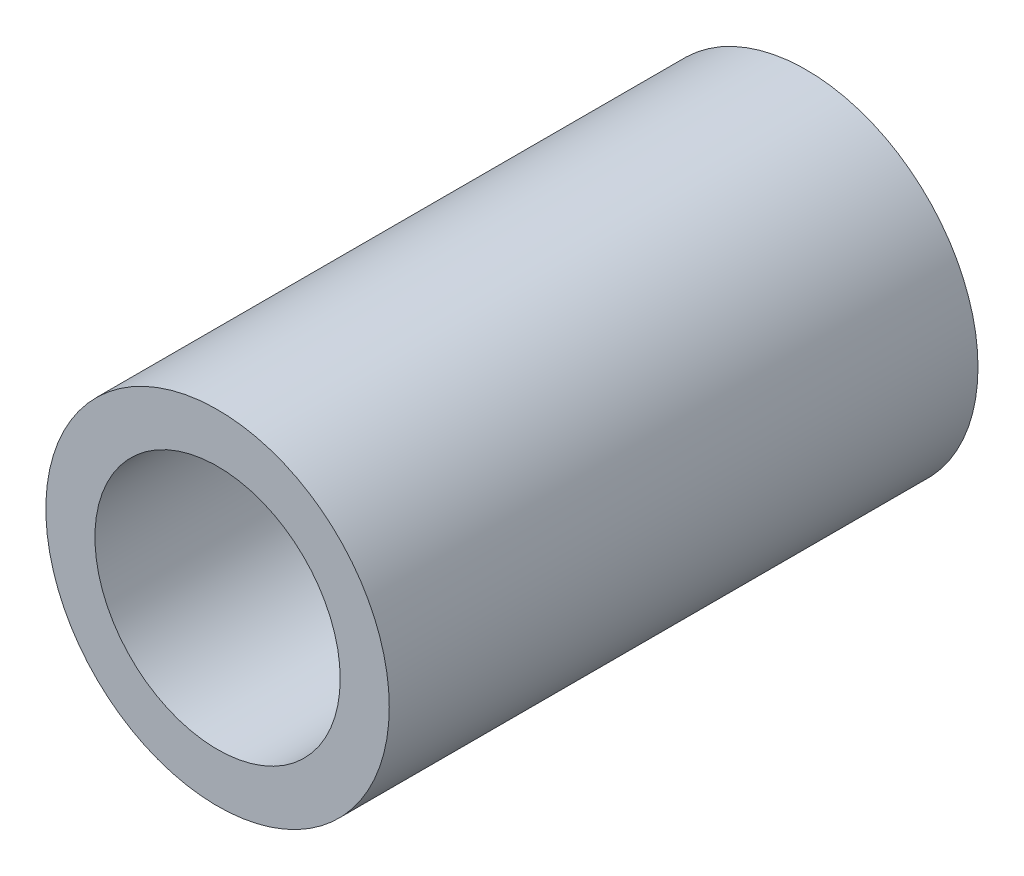
SolidWorks part; units mm, degrees
material "ABS"
ref_plane "Front" through (0, 0, 0) normal (0, 0, 1) x (1, 0, 0)
ref_plane "Top" through (0, 0, 0) normal (0, 1, 0) x (1, 0, 0)
ref_plane "Right" through (0, 0, 0) normal (1, 0, 0) x (0, 0, -1)
sketch "Esboço1" plane through (0, 0, 0) normal (0, 0, 1) x (1, 0, 0)
  circle A0 centre (0, 0) radius 3.5
  circle A1 centre (0, 0) radius 2.5
  dimension "D1" = 5
  dimension "D2" = 7
extrude "Ressalto-extrusão1" add sketch "Esboço1" along normal blind 12
